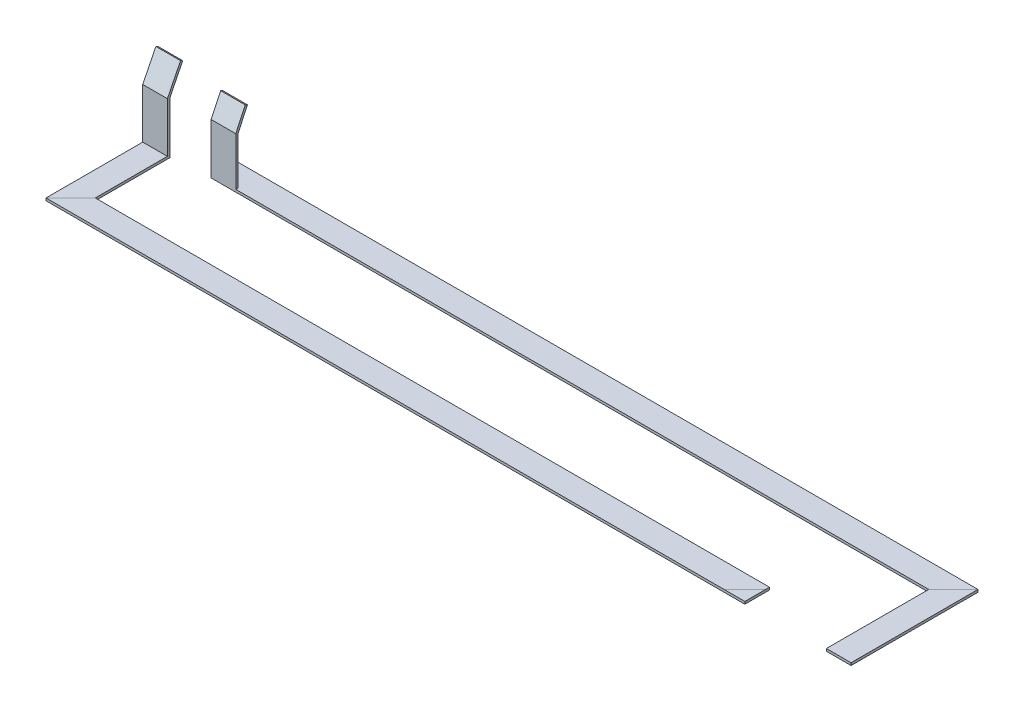
SolidWorks part; units mm, degrees
ref_plane "Alzado" through (0, 0, 0) normal (0, 0, 1) x (1, 0, 0)
ref_plane "Planta" through (0, 0, 0) normal (0, 1, 0) x (1, 0, 0)
ref_plane "Vista lateral" through (0, 0, 0) normal (1, 0, 0) x (0, 0, -1)
sketch "Croquis2" plane through (0, 0, 0) normal (0, 1, 0) x (1, 0, 0)
  line L1 (-31.75, 3.155) -> (31.75, 3.155)
  line L2 (-31.75, 3.155) -> (-31.75, -3.155)
  line L3 (-31.75, -3.155) -> (31.75, -3.155)
  line L4 (31.75, 3.155) -> (31.75, -3.155)
  line L5 (-31.75, 3.155) -> (31.75, -3.155) construction
  line L6 (-31.75, -3.155) -> (31.75, 3.155) construction
  line L7 (231.75, 3.155) -> (295.25, 3.155)
  line L8 (231.75, 3.155) -> (231.75, -3.155)
  line L9 (231.75, -3.155) -> (295.25, -3.155)
  line L10 (295.25, 3.155) -> (295.25, -3.155)
  line L11 (231.75, 3.155) -> (295.25, -3.155) construction
  line L12 (231.75, -3.155) -> (295.25, 3.155) construction
  point P0 (0, 0)
  point P6 (263.5, 0)
  dimension "D1" = 63.5
  dimension "D2" = 6.31
  dimension "D3" = 263.5
  dimension "D4" = 63.5
  dimension "D5" = 6.31
sketch3d "Croquis3D1"
  line L0 (0, 0, 0) -> (0, -567.24, 0)
  line L1 (0, -567.24, 0) -> (0, -567.24, 316.2)
  line L2 (0, -567.24, 316.2) -> (1786.7, -567.24, 316.2)
  line L3 (1786.7, -567.24, 316.2) -> (1786.7, -567.24, 578)
  line L4 (-31.75, 0, 0) -> (-31.75, -383.9185, 0) construction
  line L5 (-31.75, 0, -3.155) -> (-31.75, 0, 3.155) construction
  line L6 (-31.75, -383.9185, 0) -> (-31.75, -383.9185, 653.2834) construction
  line L7 (1786.7, -567.24, 578) -> (1786.7, -435.4728, 578)
  line L8 (1786.7, -435.4728, 578) -> (1786.7, -435.4728, 1432.0029)
  dimension "D1" = 567.24
  dimension "D2" = 316.2
  dimension "D3" = 1786.7
  dimension "D4" = 261.8
  dimension "D5" = 131.7672
  dimension "D6" = 854.0029
sweep "Barrer1" add profiles "Croquis2" path "Croquis3D1"
sketch "Croquis3" plane through (0, 0, -3.155) normal (0, 0, -1) x (-1, 0, 0)
  line L0 (-295.25, 0) -> (-295.25, -6.31)
  line L1 (-295.25, 0) -> (-295.25, -570.395) construction
  line L2 (-295.25, -6.31) -> (-231.75, -6.31)
  line L3 (-231.75, 0) -> (-231.75, -570.395) construction
  line L4 (-231.75, -6.31) -> (-231.75, 0)
  line L5 (-231.75, 0) -> (-295.25, 0)
  line L7 (-31.75, 0) -> (-31.75, -6.31)
  line L8 (-31.75, 0) -> (-31.75, -570.395) construction
  line L9 (-31.75, -6.31) -> (31.75, -6.31)
  line L10 (31.75, 0) -> (31.75, -570.395) construction
  line L11 (31.75, -6.31) -> (31.75, 0)
  line L12 (-31.75, 0) -> (31.75, 0) construction
  line L13 (31.75, 0) -> (-31.75, 0)
  dimension "D1" = 6.31
  dimension "D2" = 6.31
sketch3d "Croquis3D2"
  line L0 (31.75, -3.155, -3.155) -> (-0.201, -3.155, -3.155) construction
  line L1 (31.75, 0, -3.155) -> (31.75, -6.31, -3.155) construction
  line L2 (-0.201, -3.155, -3.155) -> (-0.201, -5.2746, -3.155) construction
  line L3 (-0.201, -3.155, -3.155) -> (-0.201, -3.155, -207.155)
  line L4 (-0.201, -3.155, -207.155) -> (-0.201, -53.155, -207.155)
  dimension "D1" = 204
  dimension "D2" = 50
sweep "Barrer4" add profiles "Croquis3" path "Croquis3D2"
sketch "Croquis4" plane through (0, 0, -210.31) normal (0, 0, -1) x (-1, 0, 0)
  line L0 (-231.75, 0) -> (-231.75, -53.155)
  line L1 (-231.75, -53.155) -> (-171.75, -53.155)
  line L2 (-171.75, -53.155) -> (-171.75, 0)
  line L3 (-171.75, 0) -> (-231.75, 0)
  dimension "D1" = 60
extrude "Saliente-Extruir1" add sketch "Croquis4" against normal blind 6.31
sketch "Croquis5" plane through (0, 0, -204) normal (0, 0, 1) x (1, 0, 0)
  line L0 (231.75, -6.31) -> (171.75, -6.31)
  line L1 (171.75, -53.155) -> (171.75, 0) construction
  line L2 (171.75, -6.31) -> (171.75, 0)
  line L3 (171.75, 0) -> (231.75, 0)
  line L4 (231.75, 0) -> (231.75, -6.31)
extrude "Cortar-Extruir1" cut sketch "Croquis5" against normal blind 6.31
sketch "Croquis6" plane through (0, -432.3178, 0) normal (0, 1, 0) x (1, 0, 0)
  circle A0 centre (1285.7, -1260.295) radius 4.75
  circle A1 centre (1495.7, -1260.295) radius 4.75
sketch "Croquis7" plane through (0, 0, 3.155) normal (0, 0, 1) x (1, 0, 0)
  line L0 (295.25, -564.085) -> (231.75, -564.085)
  line L1 (231.75, -564.085) -> (231.75, -68.8755)
  line L2 (231.75, 0) -> (231.75, -564.085) construction
  line L3 (231.75, -68.8755) -> (170.6111, -68.8755)
  line L4 (170.6111, -68.8755) -> (170.6111, 0)
  line L5 (170.6111, 0) -> (295.25, 0)
  line L6 (295.25, 0) -> (295.25, -564.085)
extrude "Cortar-Extruir2" cut sketch "Croquis7" against normal blind 502
sketch "Croquis8" plane through (0, 0, 3.155) normal (0, 0, 1) x (1, 0, 0)
  line L0 (31.75, -564.085) -> (-31.75, -564.085)
  line L1 (-31.75, -564.085) -> (-31.75, 0)
  line L2 (-31.75, 0) -> (31.75, 0)
  line L3 (31.75, 0) -> (31.75, -564.085)
extrude "Cortar-Extruir3" cut sketch "Croquis8" against normal blind 502
sketch "Croquis9" plane through (0, -432.3178, 0) normal (0, 1, 0) x (1, 0, 0)
  line L0 (1754.95, -347.95) -> (2081.95, -347.95)
  line L1 (2081.95, -20.95) -> (2081.95, -574.845) construction
  line L2 (2081.95, -347.95) -> (2081.95, -1432.0029)
  line L3 (2081.95, -1432.0029) -> (1754.95, -1432.0029)
  line L4 (1754.95, -347.95) -> (1754.95, -1432.0029)
extrude "Cortar-Extruir4" cut sketch "Croquis9" against normal blind 502
sketch "Croquis10" plane through (0, 0, -3.155) normal (0, 0, -1) x (-1, 0, 0)
  line L0 (-31.75, -564.085) -> (31.75, -564.085)
  line L1 (31.75, -564.085) -> (31.75, -570.395)
  line L2 (31.75, -570.395) -> (-31.75, -570.395)
  line L3 (-31.75, -570.395) -> (-31.75, -564.085)
extrude "Cortar-Extruir5" cut sketch "Croquis10" against normal blind 95
sketch "Croquis11" plane through (0, -564.085, 0) normal (0, 1, 0) x (1, 0, 0)
  line L0 (295.25, -20.95) -> (231.75, -20.95)
  line L1 (231.75, -3.155) -> (231.75, -84.45) construction
  line L2 (231.75, -84.45) -> (295.25, -84.45)
  line L3 (231.75, -84.45) -> (2018.45, -84.45) construction
  line L4 (295.25, -84.45) -> (295.25, -20.95)
  line L5 (295.25, -20.95) -> (295.25, 3.155)
  line L6 (295.25, 3.155) -> (231.75, 3.155)
  line L7 (231.75, 3.155) -> (231.75, -20.95)
  line M1 (295.25, -20.95) -> (295.25, -3.155)
  line M2 (295.25, -3.155) -> (295.25, 3.155)
  line M3 (295.25, 3.155) -> (231.75, 3.155)
  line M4 (231.75, 3.155) -> (231.75, -3.155)
  line M5 (231.75, -3.155) -> (231.75, -84.45)
  line M6 (231.75, -84.45) -> (295.25, -20.95)
extrude "Cortar-Extruir6" cut sketch "Croquis11" against normal blind 95 contours L2 L4 M6 | L0 M6 M5 | L0 M1 M2 M3 M4 M5
sketch "Croquis13" plane through (0, -564.085, 0) normal (0, 1, 0) x (1, 0, 0)
  line L0 (-31.75, -91.845) -> (-31.75, -347.95)
  line L1 (-31.75, -347.95) -> (88.25, -347.95)
  line L2 (-31.75, -347.95) -> (1754.95, -347.95) construction
  line L3 (88.25, -347.95) -> (88.25, -91.845)
  line L4 (88.25, -91.845) -> (-31.75, -91.845)
  dimension "D1" = 120
extrude "Cortar-Extruir7" cut sketch "Croquis13" against normal blind 95
sketch "Croquis16" plane through (0, -564.085, 0) normal (0, 1, 0) x (1, 0, 0)
  line L2 (295.25, -20.95) -> (170.25, -20.95)
  line L3 (170.25, -20.95) -> (170.25, -84.45)
  line L4 (170.25, -84.45) -> (295.25, -84.45)
  line L5 (295.25, -20.95) -> (295.25, -84.45)
  dimension "D1" = 125
extrude "Saliente-Extruir4" add sketch "Croquis16" against normal blind 6.31
sketch "Croquis17" plane through (88.25, 0, 0) normal (-1, 0, 0) x (0, 0, 1)
  line L0 (284.45, -564.085) -> (284.45, -570.395)
  line L1 (284.45, -570.395) -> (347.95, -570.395)
  line L2 (347.95, -570.395) -> (347.95, -564.085)
  line L3 (347.95, -564.085) -> (284.45, -564.085)
  line L4 (316.2, -564.085) -> (316.2, -570.395) construction
  line L5 (316.2, -570.395) -> (316.2, -567.24) construction
  line L6 (316.2, -567.24) -> (347.95, -567.24) construction
sketch3d "Croquis3D3"
  line L0 (88.25, -567.24, 316.2) -> (40.2, -567.24, 316.2)
  line L1 (40.2, -567.24, 316.2) -> (40.2, -567.24, 66.2)
  dimension "D1" = 48.05
  dimension "D2" = 250
sweep "Barrer5" add profiles "Croquis17" path "Croquis3D3"
sketch "Croquis18" plane through (8.45, 0, 0) normal (-1, 0, 0) x (0, 0, 1)
  line L0 (98.7872, -564.085) -> (98.7872, -435.523)
  line L1 (347.95, -564.085) -> (66.2, -564.085) construction
  line L2 (98.7872, -435.523) -> (64.97, -367.6227)
  line L3 (64.97, -367.6227) -> (59.3217, -370.4358)
  line L4 (59.3217, -370.4358) -> (91.8975, -435.8435)
  line L5 (91.8975, -435.8435) -> (91.8429, -564.085)
  line L6 (91.8429, -564.085) -> (98.7872, -564.085)
  dimension "D1" = 6.31
extrude "Saliente-Extruir5" add sketch "Croquis18" against normal blind 63.5
sketch "Croquis19" plane through (0, -564.085, 0) normal (0, 1, 0) x (1, 0, 0)
  line L0 (71.95, -91.8429) -> (71.95, -66.2)
  line L1 (71.95, -66.2) -> (8.45, -66.2)
  line L2 (8.45, -66.2) -> (8.45, -91.8429)
  line L3 (8.45, -91.8429) -> (71.95, -91.8429)
extrude "Cortar-Extruir8" cut sketch "Croquis19" against normal blind 63.5
sketch "Croquis20" plane through (170.25, 0, 0) normal (-1, 0, 0) x (0, 0, 1)
  line L0 (84.45, -564.085) -> (84.45, -439.8845)
  line L1 (84.45, -439.8845) -> (59.9661, -387.9255)
  line L2 (59.9661, -387.9255) -> (54.258, -390.6152)
  line L3 (54.258, -390.6152) -> (78.14, -441.2967)
  line L4 (78.14, -441.2967) -> (78.14, -564.085)
  line L5 (20.95, -564.085) -> (84.45, -564.085) construction
  line L6 (78.14, -564.085) -> (84.45, -564.085)
  dimension "D1" = 6.31
  dimension "D2" = 6.31
extrude "Saliente-Extruir6" add sketch "Croquis20" against normal blind 63.5
sketch "Croquis21" plane through (0, -564.085, 0) normal (0, 1, 0) x (1, 0, 0)
  line L0 (1818.45, -284.45) -> (1808.45, -284.45)
  line L1 (71.95, -284.45) -> (1818.45, -284.45) construction
  line L2 (1808.45, -284.45) -> (1808.45, -347.95)
  line L3 (1754.95, -347.95) -> (1818.45, -347.95) construction
  line L4 (1808.45, -347.95) -> (1818.45, -347.95)
  line L5 (1818.45, -347.95) -> (1818.45, -284.45)
  dimension "D1" = 10
extrude "Cortar-Extruir9" cut sketch "Croquis21" against normal blind 53
